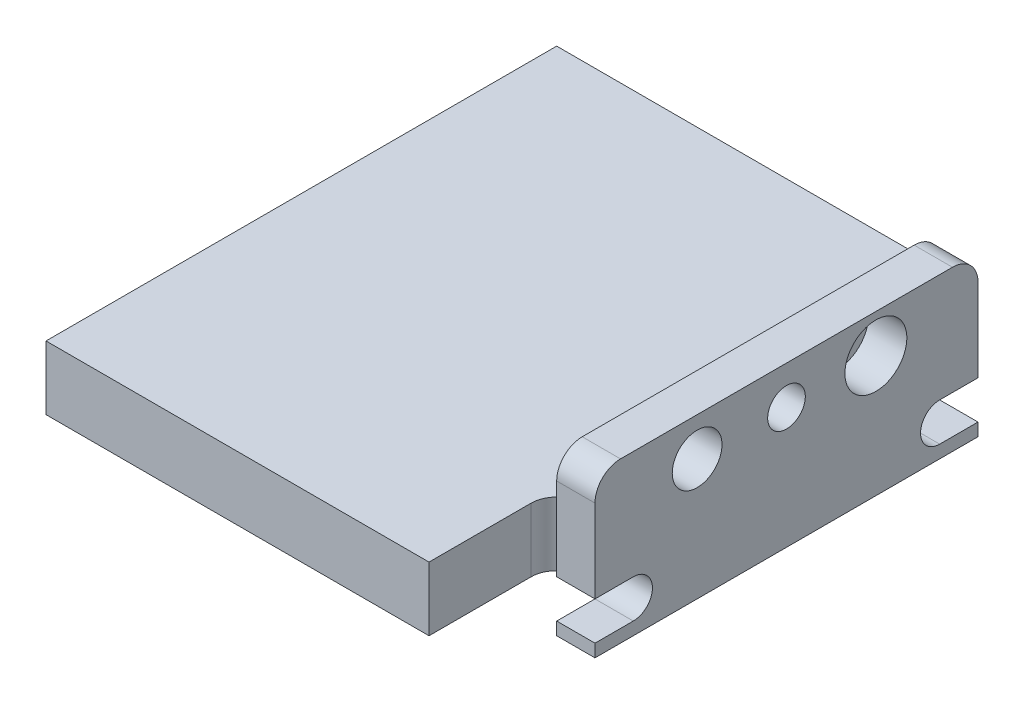
SolidWorks part; units mm, degrees
ref_plane "前视基准面" through (0, 0, 0) normal (0, 0, 1) x (1, 0, 0)
ref_plane "上视基准面" through (0, 0, 0) normal (0, 1, 0) x (1, 0, 0)
ref_plane "右视基准面" through (0, 0, 0) normal (1, 0, 0) x (0, 0, -1)
sketch "草图1" plane through (0, 0, 0) normal (1, 0, 0) x (0, 0, -1)
  line L1 (-10, 2.5) -> (10, 2.5)
  line L2 (-10, 2.5) -> (-10, -2.5)
  line L3 (-10, -2.5) -> (10, -2.5)
  line L4 (10, 2.5) -> (10, -2.5)
  line L5 (-10, 2.5) -> (10, -2.5) construction
  line L6 (-10, -2.5) -> (10, 2.5) construction
  point P0 (0, 0)
  dimension "D1" = 5
  dimension "D2" = 20
extrude "凸台-拉伸1" add sketch "草图1" against normal blind 35
sketch "草图2" plane through (0, 0, 0) normal (1, 0, 0) x (0, 0, -1)
  line L1 (-15, 10) -> (15, 10)
  line L2 (-15, 10) -> (-15, -10)
  line L3 (-15, -10) -> (15, -10)
  line L4 (15, 10) -> (15, -10)
  line L5 (-15, 10) -> (15, -10) construction
  line L6 (-15, -10) -> (15, 10) construction
  point P0 (0, 0)
  dimension "D1" = 20
  dimension "D2" = 30
extrude "凸台-拉伸2" add sketch "草图2" along normal blind 3
fillet "圆角1" radius 2 1 edges at (1.5, 10, -15)
fillet "圆角2" radius 2 1 edges at (1.5, 10, 15)
fillet "圆角3" radius 2 1 edges at (1.5, -10, -15)
fillet "圆角4" radius 2 1 edges at (1.5, -10, 15)
sketch "草图4" plane through (0, 0, 0) normal (0, 1, 0) x (1, 0, 0)
  line L0 (-71.4991, 0) -> (19.3429, 0) construction
  line L1 (-35, 20) -> (-5, 20)
  line L2 (-35, 20) -> (-35, -20)
  line L3 (-35, -20) -> (-5, -20)
  line L4 (-5, 20) -> (-5, -20)
  line L5 (0, 13) -> (0, -13) construction
  point P7 (-35, 0)
  dimension "D1" = 30
  dimension "D2" = 20
  dimension "D3" = 5
extrude "凸台-拉伸3" add sketch "草图4" along normal mid plane 5
fillet "圆角5" radius 2 1 edges at (-5, 0, -10)
fillet "圆角6" radius 2 1 edges at (-5, 0, 10)
sketch "草图5" plane through (0, 0, 0) normal (1, 0, 0) x (0, 0, -1)
  line L0 (-15, 8) -> (-15, -8) construction
  line L1 (-12, -1.5) -> (-15, -1.5)
  line L2 (0, -12.7004) -> (0, 18.7249) construction
  line L3 (-12, 1.5) -> (-15, 1.5)
  line L4 (-15, -1.5) -> (-15, 1.5)
  line L5 (-12, -1.5) -> (-15, 1.5) construction
  line L6 (-12, 1.5) -> (-15, -1.5) construction
  line L7 (-18.2451, 0) -> (18.228, 0) construction
  line L8 (12, 1.5) -> (15, 1.5)
  line L9 (12, -1.5) -> (15, -1.5)
  line L10 (15, -1.5) -> (15, 1.5)
  arc A0 (-12, -1.5) -> (-12, 1.5) centre (-12, 0) ccw
  arc A1 (12, -1.5) -> (12, 1.5) centre (12, 0) cw
  point P0 (-13.5, 0)
  point P8 (-15, 0)
  point P14 (-13.5, 1.5)
  point P19 (13.5, 1.5)
  dimension "D1" = 3
  dimension "D2" = 3
extrude "切除-拉伸2" cut sketch "草图5" along normal blind 3
sketch "草图6" plane through (0, 0, 0) normal (1, 0, 0) x (0, 0, -1)
  line L0 (0, -12.2212) -> (0, 15.5615) construction
  line L1 (-13, -10) -> (13, -10) construction
  line L2 (-7, -12.2212) -> (-7, 15.5615) construction
  line L3 (7, -12.2212) -> (7, 15.5615) construction
  line L5 (23.6468, 0) -> (-26.4286, 0) construction
  line L6 (-17.956, -7) -> (17.956, -7) construction
  circle A0 centre (0, -7) radius 1.475
  circle A1 centre (-7, -7) radius 1.95
  circle A2 centre (7, -7) radius 2.425
  circle A3 centre (7, 7) radius 2.425
  circle A4 centre (0, 7) radius 1.475
  circle A5 centre (-7, 7) radius 1.95
  point P19 (0, 0)
  point P20 (0, 0)
  point P21 (0, 0)
  point P22 (0, 0)
  point P23 (0, 0)
  point P24 (0, 0)
  dimension "D1" = 2.95
  dimension "D4" = 4.85
  dimension "D5" = 3.9
  dimension "D6" = 7
  dimension "D2" = 3
  dimension "D3" = 7
extrude "切除-拉伸3" cut sketch "草图6" along normal blind 3
sketch "草图8" plane through (0, 0, -15) normal (0, 0, -1) x (-1, 0, 0)
  line L0 (0, -8) -> (0, -1.5) construction
  line L1 (0, -2.5) -> (-3, -2.5)
  line L2 (0, -2.5) -> (0, -10)
  line L3 (0, -10) -> (-3, -10)
  line L4 (-3, -2.5) -> (-3, -10)
  line L5 (0, -10) -> (-3, -10) construction
  line L6 (-3, -8) -> (-3, -1.5) construction
  line L7 (3, -2.5) -> (0, -2.5) construction
extrude "切除-拉伸4" cut sketch "草图8" against normal blind 30
